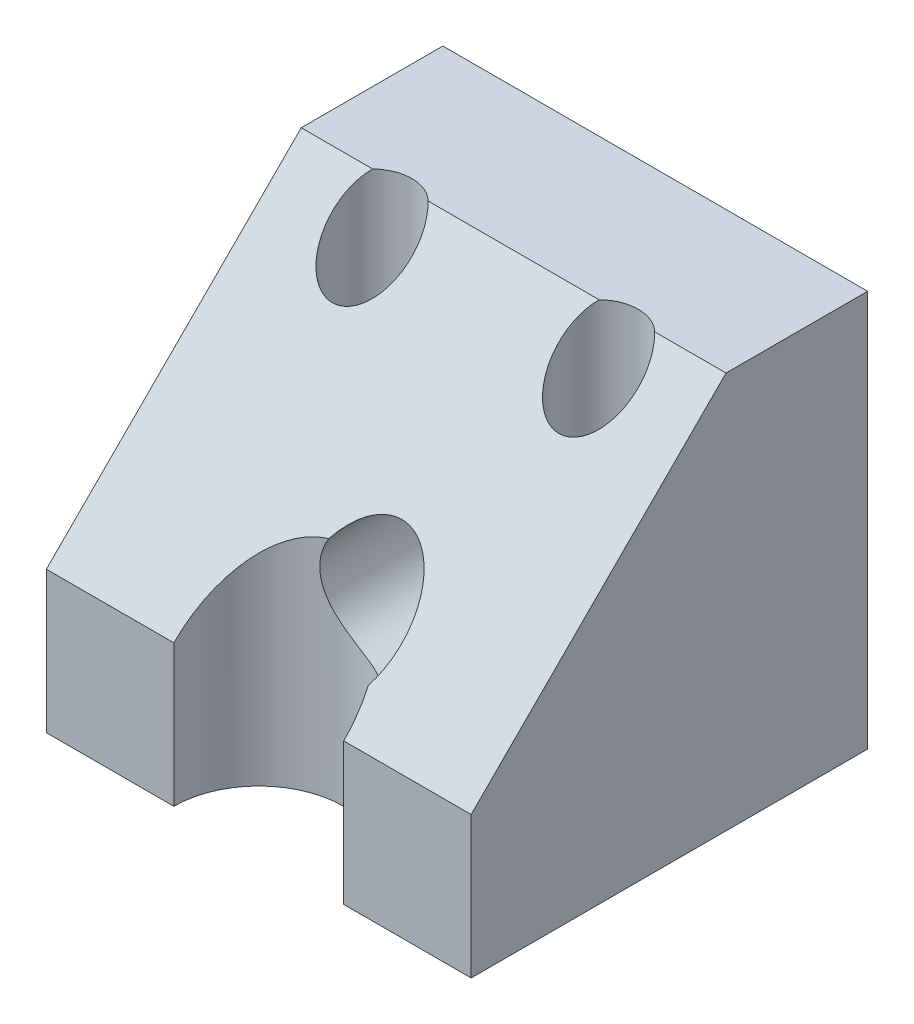
SolidWorks part; units mm, degrees
material "PLA"
ref_plane "前视基准面" through (0, 0, 0) normal (0, 0, 1) x (1, 0, 0)
ref_plane "上视基准面" through (0, 0, 0) normal (0, 1, 0) x (1, 0, 0)
ref_plane "右视基准面" through (0, 0, 0) normal (1, 0, 0) x (0, 0, -1)
sketch "草图1" plane through (0, 0, 0) normal (1, 0, 0) x (0, 0, -1)
  line L0 (-14, 0) -> (0, 0)
  line L1 (0, 0) -> (0, 14)
  line L2 (0, 14) -> (-5, 14)
  line L3 (-5, 14) -> (-14, 5)
  line L4 (-14, 5) -> (-14, 0)
  line L5 (0, 7) -> (-6, 7) construction
  line L6 (-6, 7) -> (-6, 0) construction
  dimension "D1" = 6
  dimension "D2" = 7
  dimension "D3" = 14
  dimension "D4" = 14
  dimension "D5" = 135
  dimension "D6" = 5
extrude "凸台-拉伸1" add sketch "草图1" along normal blind 15
sketch "草图2" plane through (0, 0, 0) normal (0, -1, 0) x (1, 0, 0)
  line L0 (3.5, 6) -> (11.5, 6) construction
  line L1 (15, 0) -> (0, 0) construction
  circle A0 centre (11.5, 6) radius 1.4
  circle A1 centre (3.5, 6) radius 1.4
  point P2 (7.5, 6)
  point P5 (7.5, 0)
  dimension "D3" = 2.8
  dimension "D1" = 6
  dimension "D2" = 8
extrude "切除-拉伸1" cut sketch "草图2" against normal through all and the other way through all
sketch "草图3" plane through (0, 0, 0) normal (0, 0, -1) x (-1, 0, 0)
  line L0 (-15, 0) -> (-15, 14) construction
  line L1 (-15, 0) -> (0, 0) construction
  circle A0 centre (-8.65, 7) radius 1.9
  dimension "D3" = 3.8
  dimension "D1" = 7
  dimension "D2" = 6.35
extrude "切除-拉伸2" cut sketch "草图3" against normal through all
sketch "草图4" plane through (0, 0, 0) normal (0, -1, 0) x (1, 0, 0)
  line L0 (15, 14) -> (0, 14) construction
  circle A0 centre (7.5, 14) radius 3
  dimension "D1" = 6
extrude "切除-拉伸3" cut sketch "草图4" against normal through all
